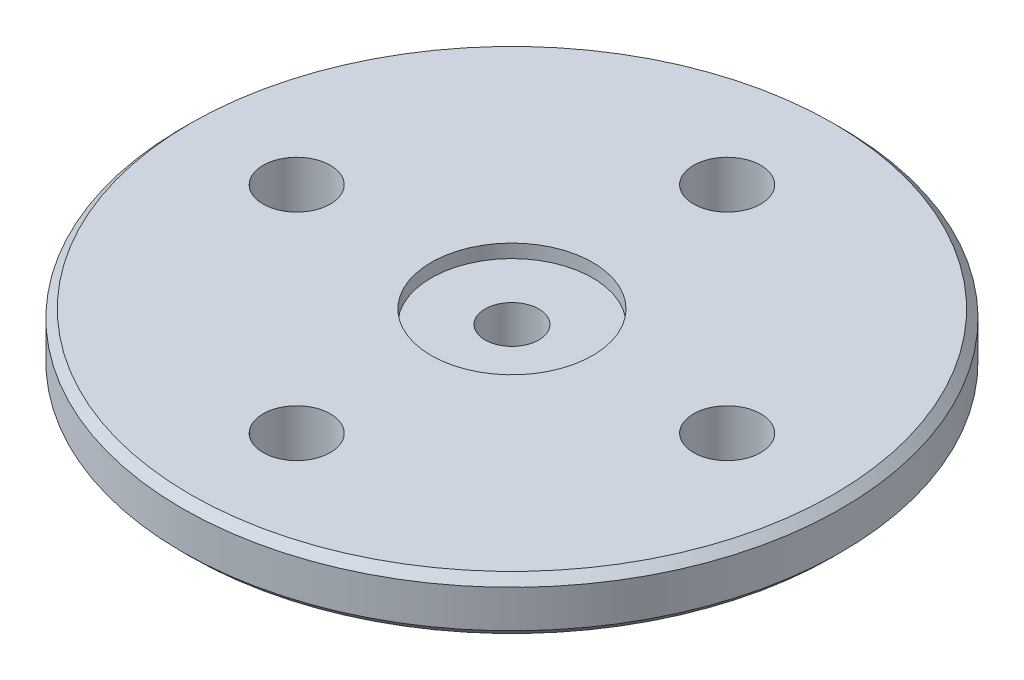
SolidWorks part; units mm, degrees
material "普通碳钢"
ref_plane "前视基准面" through (0, 0, 0) normal (0, 0, 1) x (1, 0, 0)
ref_plane "上视基准面" through (0, 0, 0) normal (0, 1, 0) x (1, 0, 0)
ref_plane "右视基准面" through (0, 0, 0) normal (1, 0, 0) x (0, 0, -1)
sketch "草图1" plane through (0, 0, 0) normal (0, 1, 0) x (1, 0, 0)
  circle A0 centre (0, 0) radius 4
  circle A1 centre (0, 0) radius 1
  dimension "D1" = 8
  dimension "D2" = 2
extrude "凸台-拉伸1" add sketch "草图1" along normal blind 5
sketch "草图2" plane through (0, 5, 0) normal (0, 1, 0) x (1, 0, 0)
  line L0 (0, 8) -> (0, 0) construction
  circle A0 centre (0, 0) radius 4 construction
  circle A1 centre (0, 0) radius 4
  circle A2 centre (0, 0) radius 12.25
  circle A3 centre (0, 8) radius 1.25
  circle A4 centre (8, 0) radius 1.25
  circle A5 centre (0, -8) radius 1.25
  circle A6 centre (-8, 0) radius 1.25
  circle A7 centre (0, 0) radius 8 construction
  point P15 (0, 0)
  dimension "D1" = 24.5
  dimension "D2" = 2.5
  dimension "D4" = 16
  dimension "D3" = 4
extrude "凸台-拉伸2" add sketch "草图2" against normal blind 2
chamfer "倒角1" distance 0.3 angle 45 4 edges at (0, 0, 4) (0, 3, 4) (0, 3, 12.25) (0, 5, 12.25)
sketch "草图3" plane through (0, 5, 0) normal (0, 1, 0) x (1, 0, 0)
  circle A0 centre (0, 0) radius 3
  dimension "D1" = 6
extrude "切除-拉伸1" cut sketch "草图3" against normal blind 0.5
sketch "草图4" plane through (0, 0, 0) normal (0, -1, 0) x (1, 0, 0)
  circle A0 centre (0, 0) radius 2.9
  dimension "D1" = 5.8
extrude "切除-拉伸2" cut sketch "草图4" against normal blind 3
